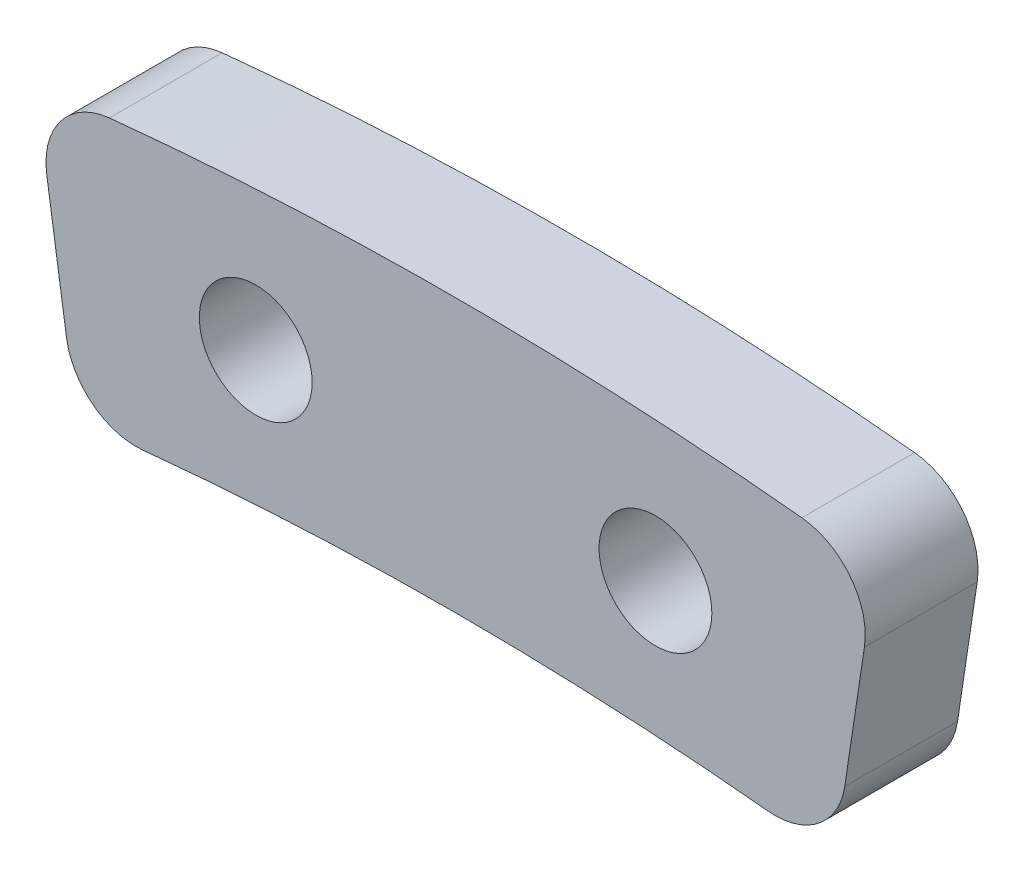
SolidWorks part; units mm, degrees
material "ABS"
ref_plane "Front Plane" through (0, 0, 0) normal (0, 0, 1) x (1, 0, 0)
ref_plane "Top Plane" through (0, 0, 0) normal (0, 1, 0) x (1, 0, 0)
ref_plane "Right Plane" through (0, 0, 0) normal (1, 0, 0) x (0, 0, -1)
sketch "Sketch1" plane through (0, 0, 0) normal (0, 0, 1) x (1, 0, 0)
  line L0 (-14.9042, 98.8831) -> (-12.9667, 86.0283) construction
  line L1 (12.9667, 86.0283) -> (14.9042, 98.8831) construction
  line L2 (0, 100) -> (0, 0) construction
  line L3 (-11.9086, 96.641) -> (-10.754, 88.9805)
  line L4 (10.754, 88.9805) -> (11.9086, 96.641)
  circle A0 centre (0, 0) radius 87 construction
  circle A1 centre (0, 0) radius 100 construction
  circle A2 centre (0, 0) radius 87 construction
  circle A3 centre (0, 0) radius 100 construction
  circle A4 centre (0, 0) radius 100 construction
  arc A5 (14.9042, 98.8831) -> (-14.9042, 98.8831) centre (0, 0) ccw construction
  arc A6 (12.9667, 86.0283) -> (-12.9667, 86.0283) centre (0, 0) ccw construction
  arc A7 (10.754, 88.9805) -> (-10.754, 88.9805) centre (0, 0) ccw
  arc A8 (11.9086, 96.641) -> (-11.9086, 96.641) centre (0, 0) ccw
  dimension "D1" = 17.143
  dimension "D2" = 2.628
extrude "Boss-Extrude1" add sketch "Sketch1" along normal up to vertex (3.2 mm away)
fillet "Fillet1" radius 2 4 edges at (11.9086, 96.641, 1.6) (10.754, 88.9805, 1.6) (-10.754, 88.9805, 1.6) (-11.9086, 96.641, 1.6)
sketch "Sketch2" plane through (0, 0, 3.2) normal (0, 0, 1) x (1, 0, 0)
  line L2 (11.0404, 90.8806) -> (11.5991, 94.5874) construction
  line L3 (-11.5991, 94.5874) -> (-11.0404, 90.8806) construction
  line L4 (-11.3197, 92.734) -> (-5.6703, 93.2501) construction
  line L5 (-5.6703, 93.2501) -> (0, 93.4223) construction
  line L6 (0, 93.4223) -> (5.6703, 93.2501) construction
  line L7 (5.6703, 93.2501) -> (11.3197, 92.734) construction
  arc A0 (-11.3197, 92.734) -> (11.3197, 92.734) centre (0, 0) cw construction
  arc A2 (9.8232, 96.8752) -> (-9.8232, 96.8752) centre (0, 0) ccw construction
  circle A3 centre (-5.6703, 93.2501) radius 1.6
  circle A4 centre (5.6703, 93.2501) radius 1.6
  dimension "D1" = 3.2
extrude "Cut-Extrude1" cut sketch "Sketch2" against normal through all
equation "\"D1@Sketch1\"=360 / 21"
